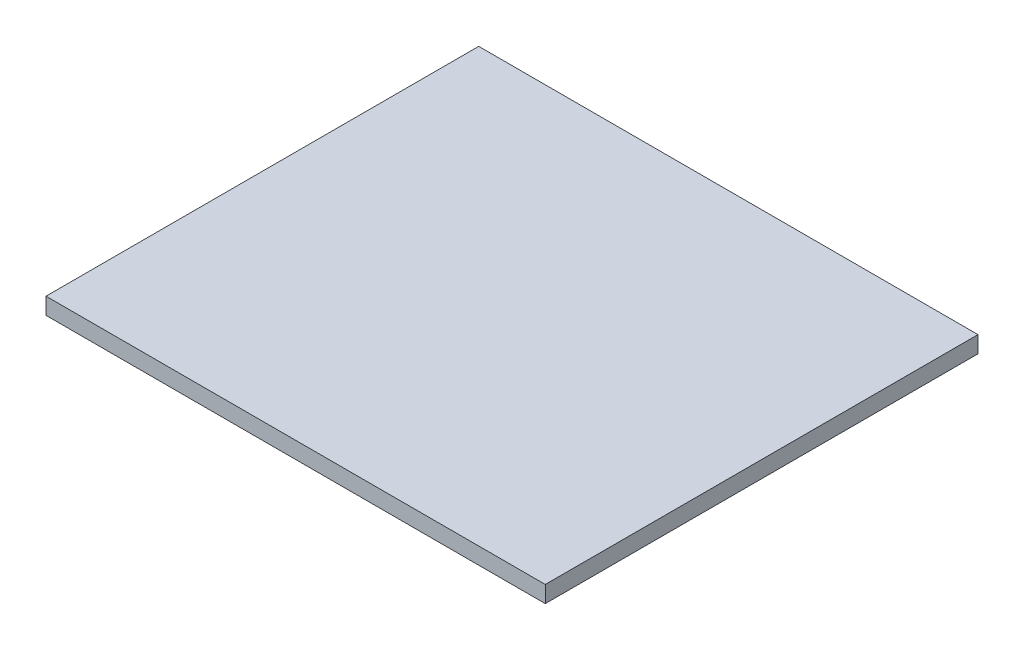
SolidWorks part; units mm, degrees
ref_plane "Front Plane" through (0, 0, 0) normal (0, 0, 1) x (1, 0, 0)
ref_plane "Top Plane" through (0, 0, 0) normal (0, 1, 0) x (1, 0, 0)
ref_plane "Right Plane" through (0, 0, 0) normal (1, 0, 0) x (0, 0, -1)
sketch "Sketch1" plane through (0, 0, 0) normal (1, 0, 0) x (0, 0, -1)
  line L1 (-12.5242, 0.3017) -> (13.4758, 0.3017)
  line L2 (-12.5242, 0.3017) -> (-12.5242, 1.3017)
  line L3 (-12.5242, 1.3017) -> (13.4758, 1.3017)
  line L4 (13.4758, 0.3017) -> (13.4758, 1.3017)
  dimension "D1" = 26
  dimension "D2" = 1
extrude "Boss-Extrude1" add sketch "Sketch1" along normal mid plane 30
